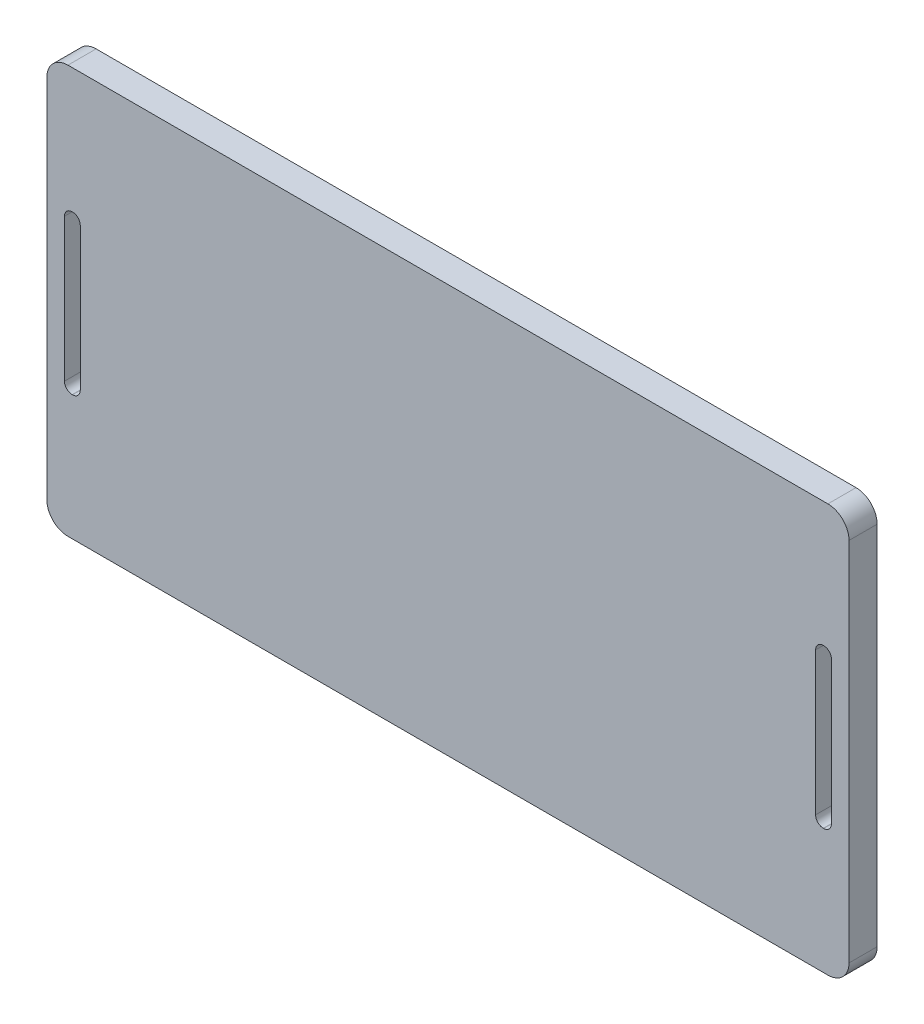
SolidWorks part; units mm, degrees
ref_plane "Front Plane" through (0, 0, 0) normal (0, 0, 1) x (1, 0, 0)
ref_plane "Top Plane" through (0, 0, 0) normal (0, 1, 0) x (1, 0, 0)
ref_plane "Right Plane" through (0, 0, 0) normal (1, 0, 0) x (0, 0, -1)
sketch "Croquis2" plane through (0, 0, 0) normal (0, 0, 1) x (1, 0, 0)
  line L2 (722.8356, 817.665) -> (722.8356, 716.5636) construction
  line L3 (614.8356, 709.1143) -> (830.8356, 709.1143)
  line L4 (608.8356, 715.1143) -> (608.8356, 819.1143)
  line L5 (614.8356, 825.1143) -> (830.8356, 825.1143)
  line L6 (836.8356, 715.1143) -> (836.8356, 819.1143)
  line L7 (608.8356, 709.1143) -> (836.8356, 825.1143) construction
  line L8 (608.8356, 825.1143) -> (836.8356, 709.1143) construction
  arc A0 (830.8356, 825.1143) -> (836.8356, 819.1143) centre (830.8356, 819.1143) cw
  arc A1 (836.8356, 715.1143) -> (830.8356, 709.1143) centre (830.8356, 715.1143) cw
  arc A2 (614.8356, 709.1143) -> (608.8356, 715.1143) centre (614.8356, 715.1143) cw
  arc A3 (614.8356, 825.1143) -> (608.8356, 819.1143) centre (614.8356, 819.1143) ccw
  point P0 (722.8356, 767.1143)
  dimension "D3" = 6
  dimension "D1" = 228
  dimension "D2" = 116
extrude "Saliente-Extruir1" add sketch "Croquis2" along normal blind 8
sketch "Croquis3" plane through (0, 0, 0) normal (0, 0, -1) x (-1, 0, 0)
  line L0 (-836.8356, 767.1143) -> (-608.8356, 767.1143) construction
  line L1 (-836.8356, 715.1143) -> (-836.8356, 819.1143) construction
  line L2 (-608.8356, 819.1143) -> (-608.8356, 715.1143) construction
  line L3 (-722.8356, 825.1143) -> (-722.8356, 709.1143) construction
  line L4 (-616.1356, 744.6143) -> (-616.0356, 744.6143)
  line L5 (-618.3356, 746.8143) -> (-618.3356, 787.4143)
  line L6 (-616.1356, 789.6143) -> (-616.0356, 789.6143)
  line L7 (-613.8356, 746.8143) -> (-613.8356, 787.4143)
  line L8 (-618.3356, 744.6143) -> (-613.8356, 789.6143) construction
  line L9 (-618.3356, 789.6143) -> (-613.8356, 744.6143) construction
  line L10 (-830.8356, 825.1143) -> (-614.8356, 825.1143) construction
  line L11 (-614.8356, 709.1143) -> (-830.8356, 709.1143) construction
  line L12 (-829.5356, 789.6143) -> (-829.6356, 789.6143)
  line L13 (-831.8356, 746.8143) -> (-831.8356, 787.4143)
  line L14 (-829.5356, 744.6143) -> (-829.6356, 744.6143)
  line L15 (-827.3356, 746.8143) -> (-827.3356, 787.4143)
  arc A0 (-616.1356, 744.6143) -> (-618.3356, 746.8143) centre (-616.1356, 746.8143) cw
  arc A1 (-616.0356, 744.6143) -> (-613.8356, 746.8143) centre (-616.0356, 746.8143) ccw
  arc A2 (-613.8356, 787.4143) -> (-616.0356, 789.6143) centre (-616.0356, 787.4143) ccw
  arc A3 (-616.1356, 789.6143) -> (-618.3356, 787.4143) centre (-616.1356, 787.4143) ccw
  arc A4 (-831.8356, 787.4143) -> (-829.6356, 789.6143) centre (-829.6356, 787.4143) cw
  arc A5 (-829.6356, 744.6143) -> (-831.8356, 746.8143) centre (-829.6356, 746.8143) cw
  arc A6 (-829.5356, 744.6143) -> (-827.3356, 746.8143) centre (-829.5356, 746.8143) ccw
  arc A7 (-829.5356, 789.6143) -> (-827.3356, 787.4143) centre (-829.5356, 787.4143) cw
  point P6 (-616.0856, 767.1143)
  dimension "D3" = 2.2
  dimension "D1" = 4.5
  dimension "D2" = 5
  dimension "D4" = 45
extrude "Cortar-Extruir1" cut sketch "Croquis3" against normal blind 10
ref_plane "Plano1" through (722.8356, 0, 0) normal (-1, 0, 0) x (0, 0, 1)
ref_plane "Plano2" through (0, 767.1143, 0) normal (0, -1, 0) x (-1, 0, 0)
